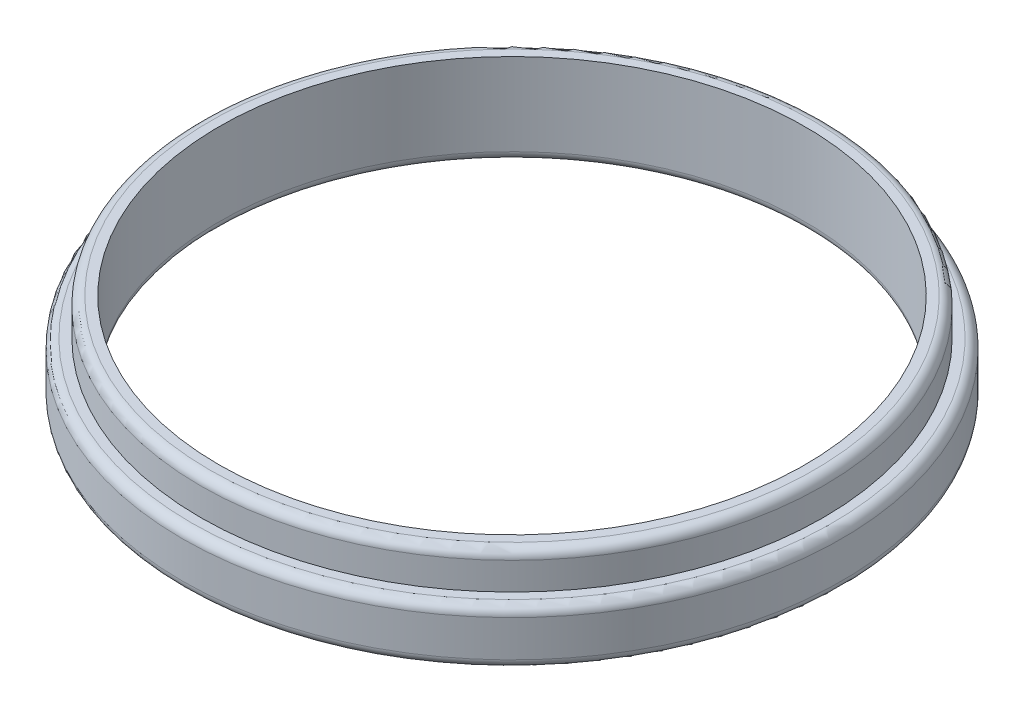
SolidWorks part; units mm, degrees
ref_plane "Alzado" through (0, 0, 0) normal (0, 0, 1) x (1, 0, 0)
ref_plane "Planta" through (0, 0, 0) normal (0, 1, 0) x (1, 0, 0)
ref_plane "Vista lateral" through (0, 0, 0) normal (1, 0, 0) x (0, 0, -1)
sketch "Croquis1" plane through (0, 0, 0) normal (0, 1, 0) x (1, 0, 0)
  circle A0 centre (0, 0) radius 9
  dimension "D1" = 18
extrude "Saliente-Extruir1" add sketch "Croquis1" along normal blind 1.5 contours A0
sketch "Croquis2" plane through (0, 1.5, 0) normal (0, 1, 0) x (1, 0, 0)
  circle A0 centre (0, 0) radius 8.5
  dimension "D1" = 17
extrude "Saliente-Extruir2" add sketch "Croquis2" along normal blind 1
shell "Vaciado1" thickness 1
sketch "Croquis3" plane through (0, 2.5, 0) normal (0, 1, 0) x (1, 0, 0)
  circle A0 centre (0, 0) radius 8
  dimension "D1" = 16
extrude "Cortar-Extruir1" cut sketch "Croquis3" against normal through all
fillet "Redondeo1" radius 0.25 1 edges at (0, 1.5, 9)
fillet "Redondeo3" radius 0.25 1 edges at (0, 2.5, 8.5)
fillet "Redondeo4" radius 0.25 1 edges at (0, 0, 9)
fillet "Redondeo5" radius 0.25 1 edges at (0, 0, 8)
